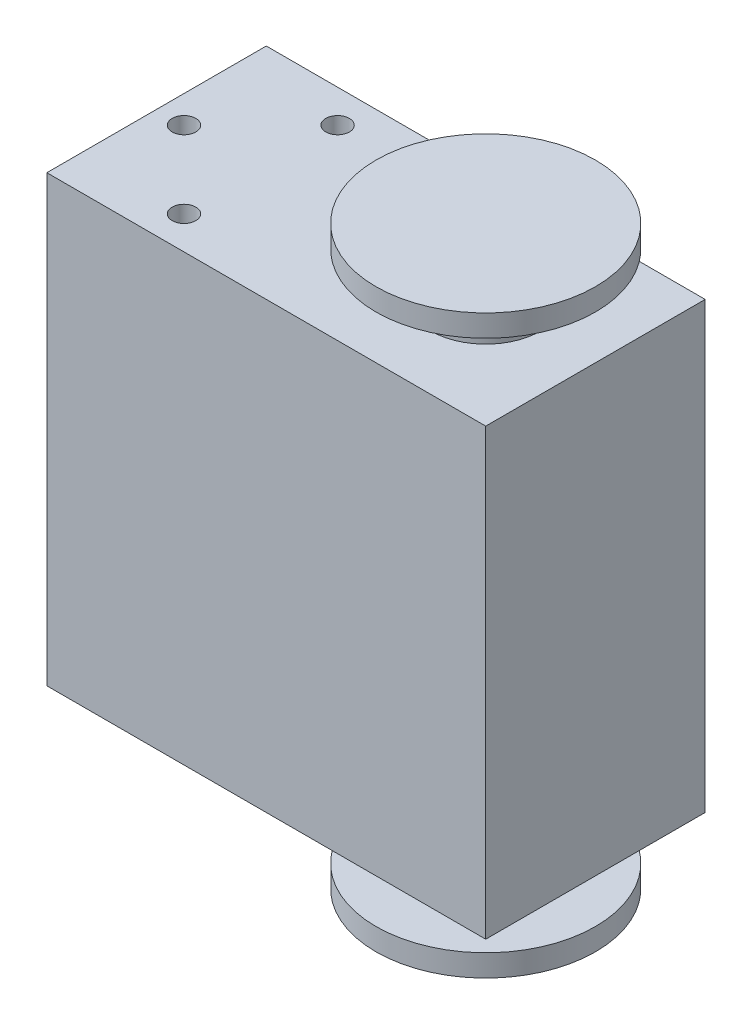
SolidWorks part; units mm, degrees
ref_plane "Front Plane" through (0, 0, 0) normal (0, 0, 1) x (1, 0, 0)
ref_plane "Top Plane" through (0, 0, 0) normal (0, 1, 0) x (1, 0, 0)
ref_plane "Right Plane" through (0, 0, 0) normal (1, 0, 0) x (0, 0, -1)
sketch "Sketch1" plane through (0, 0, 0) normal (0, 0, 1) x (1, 0, 0)
  line L1 (0, 0) -> (40, 0)
  line L2 (0, 0) -> (0, 40.5)
  line L3 (0, 40.5) -> (40, 40.5)
  line L4 (40, 0) -> (40, 40.5)
  dimension "D1" = 40.5
  dimension "D2" = 40
extrude "Boss-Extrude1" add sketch "Sketch1" along normal blind 20
sketch "Sketch2" plane through (0, 40.5, 0) normal (0, 1, 0) x (1, 0, 0)
  line L0 (40, -20) -> (40, 0) construction
  circle A0 centre (30, -10) radius 10
  dimension "D1" = 20
extrude "Boss-Extrude2" add sketch "Sketch2" along normal blind 6 and the other way blind 46.5
sketch "Sketch3" plane through (0, 0, 0) normal (0, -1, 0) x (-1, 0, 0)
  line L1 (0, -20) -> (0, 0) construction
  line L2 (0, -20) -> (-30, -20) construction
  circle A0 centre (-17.5, -2.5) radius 1
  circle A1 centre (-17.5, -17.5) radius 1
  circle A2 centre (-2.5, -17.5) radius 1
  circle A3 centre (-2.5, -2.5) radius 1
  dimension "D3" = 2
  dimension "D4" = 2.5
  dimension "D1" = 15
  dimension "D2" = 15
  dimension "D5" = 2.5
extrude "Cut-Extrude1" cut sketch "Sketch3" against normal blind 5
sketch "Sketch4" plane through (0, 40.5, 0) normal (0, 1, 0) x (1, 0, 0)
  line L0 (9.5, -17) -> (9.5, -3) construction
  line L1 (0, -20) -> (0, 0) construction
  line L2 (30, 0) -> (0, 0) construction
  circle A0 centre (2.5, -10) radius 1.0762
  circle A1 centre (9.5, -17) radius 1.0762
  circle A2 centre (9.5, -3) radius 1.0762
  dimension "D4" = 2.5
  dimension "D5" = 3
  dimension "D1" = 14
  dimension "D2" = 7
  dimension "D3" = 7
extrude "Cut-Extrude2" cut sketch "Sketch4" against normal blind 5
sketch "Sketch5" plane through (0, 40.5, 0) normal (0, 1, 0) x (1, 0, 0)
  circle A0 centre (30, -10) radius 10
  circle A1 centre (30, -10) radius 5
  dimension "D1" = 10
extrude "Cut-Extrude3" cut sketch "Sketch5" along normal blind 4
ref_plane "Plane1" through (0, 20.25, 0) normal (0, 1, 0) x (1, 0, 0)
mirror "Mirror1" about plane through (0, 20.25, 0) normal (0, 1, 0) of "Cut-Extrude3"
